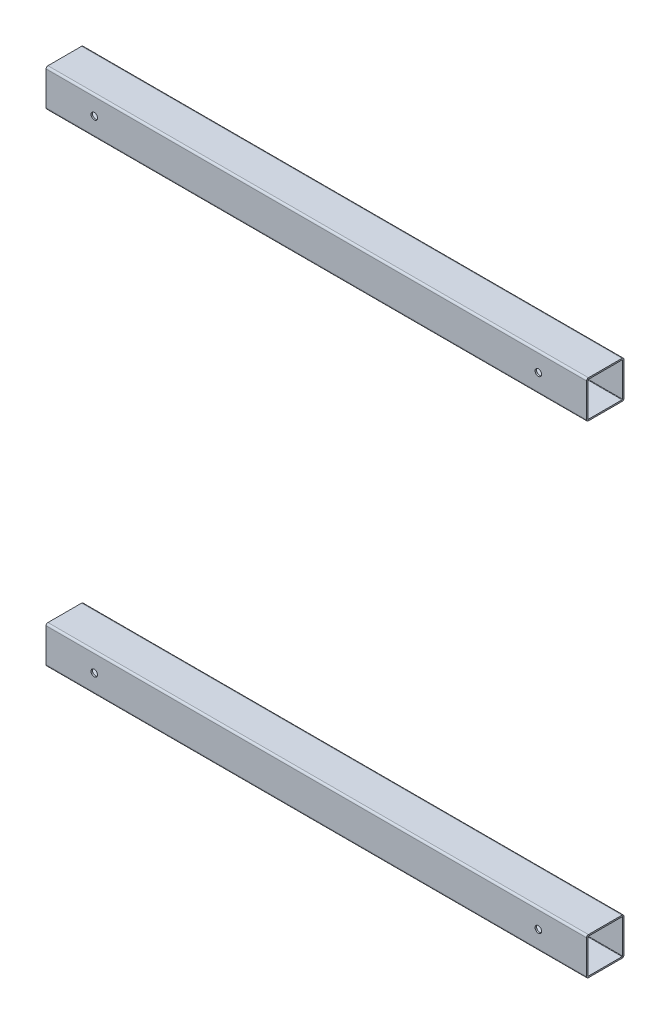
SolidWorks part; units mm, degrees
material "AISI 1020"
material "AISI 1020"
ref_plane "Plano frontal" through (0, 0, 0) normal (0, 0, 1) x (1, 0, 0)
ref_plane "Plano superior" through (0, 0, 0) normal (0, 1, 0) x (1, 0, 0)
ref_plane "Plano direito" through (0, 0, 0) normal (1, 0, 0) x (0, 0, -1)
other "Caixa delimitadora"
ref_plane "Default Plane" through (-289.0268, -20, -20) normal (0, 1, 0) x (1, 0, 0)
sketch "Esboço3" plane through (0, 0, 0) normal (0, 0, 1) x (1, 0, 0)
  line L0 (-289.0268, 0) -> (289.0268, 0)
  line L1 (-289.0268, -515.7728) -> (289.0268, -515.7728)
  point P6 (0, 0)
other " C:\\USERS\\RAULSTAR\\MEU DRIVE\\TEMPLATES\\BIBLIOTECA SOLDAGEM SOLIDWORKS\\METALON\\QUADRADO\\40 X 40 X 1,55 - ESTÁ FALTANDO(1)"
ref_plane "Plano1" through (-289.0268, 0, 0) normal (1, 0, 0) x (0, 1, 0)
sketch "Esboço1" plane through (-289.0268, 0, 0) normal (1, 0, 0) x (0, 1, 0)
  line L0 (-18, -18.45) -> (18, -18.45)
  line L1 (-18.45, -18) -> (-18.45, 18)
  line L2 (18, 18.45) -> (-18, 18.45)
  line L3 (18.45, 18) -> (18.45, -18)
  line L4 (-18, -20) -> (18, -20)
  line L5 (-20, -18) -> (-20, 18)
  line L6 (18, 20) -> (-18, 20)
  line L7 (20, 18) -> (20, -18)
  line L8 (-20, 0) -> (-18.45, 0) construction
  line L9 (-18.45, 0) -> (18.45, 0) construction
  line L10 (18.45, 0) -> (20, 0) construction
  line L11 (0, 20) -> (0, 18.45) construction
  line L12 (0, 18.45) -> (0, -18.45) construction
  line L13 (0, -18.45) -> (0, -20) construction
  arc A0 (20, 18) -> (18, 20) centre (18, 18) ccw
  arc A1 (18, -20) -> (20, -18) centre (18, -18) ccw
  arc A2 (-20, -18) -> (-18, -20) centre (-18, -18) ccw
  arc A3 (-18, 20) -> (-20, 18) centre (-18, 18) ccw
  arc A4 (-18, 18.45) -> (-18.45, 18) centre (-18, 18) ccw
  arc A5 (18.45, 18) -> (18, 18.45) centre (18, 18) ccw
  arc A6 (18, -18.45) -> (18.45, -18) centre (18, -18) ccw
  arc A7 (-18.45, -18) -> (-18, -18.45) centre (-18, -18) ccw
  point P32 (0, 0)
  point P33 (0, 0)
  dimension "D1" = 2
  dimension "D2" = 40
  dimension "D3" = 40
  dimension "D4" = 1.55
sketch "Esboço4" plane through (0, 0, -20) normal (0, 0, -1) x (-1, 0, 0)
  line L0 (289.0268, 0) -> (-289.0268, 0) construction
  line L1 (0, 0) -> (0, -20) construction
  line L2 (-289.0268, -20) -> (289.0268, -20) construction
  line L3 (289.0268, -515.7728) -> (-289.0268, -515.7728) construction
  line L5 (289.0268, -18) -> (289.0268, 18) construction
  circle A0 centre (-237.5, 0) radius 3.5
  circle A1 centre (237.5, 0) radius 3.5
  circle A2 centre (-237.5, -515.7728) radius 3.5
  circle A3 centre (237.5, -515.7728) radius 3.5
  dimension "D1" = 7
  dimension "D2" = 51.5268
extrude "Corte-extrusão1" cut sketch "Esboço4" against normal through all both and the other way through all
equation "\"D3@Esboço1\"=\"D2@Esboço1\""
